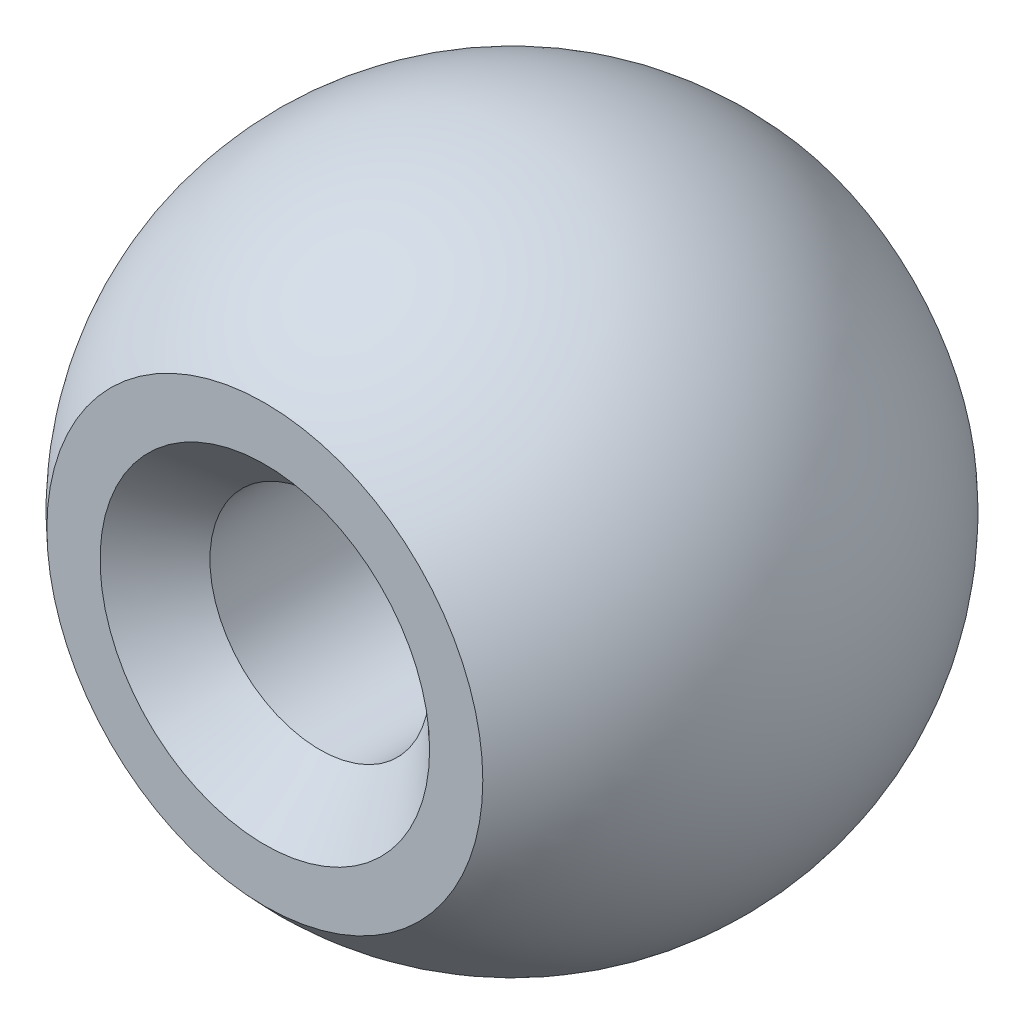
SolidWorks part; units mm, degrees
material "AISI 1020"
ref_plane "Front Plane" through (0, 0, 0) normal (0, 0, 1) x (1, 0, 0)
ref_plane "Top Plane" through (0, 0, 0) normal (0, 1, 0) x (1, 0, 0)
ref_plane "Right Plane" through (0, 0, 0) normal (1, 0, 0) x (0, 0, -1)
sketch "Sketch1" plane through (0, 0, 0) normal (1, 0, 0) x (0, 0, -1)
  line L0 (-9.663, 0) -> (9.663, 0) construction
  line L3 (-4.5, 3.9686) -> (-4.5, 0)
  line L5 (4.5, 3.9686) -> (4.5, 0)
  line L6 (0, -5) -> (0, 5) construction
  line L7 (-4.5, 0) -> (4.5, 0) construction
  line L9 (-4.5, 0) -> (4.5, 0)
  arc A2 (4.5, 3.9686) -> (-4.5, 3.9686) centre (0, 0) ccw
  point P4 (0, 0)
  dimension "D1" = 6
  dimension "D2" = 4.5
  dimension "D4" = 9
revolve "Revolve1" add sketch "Sketch1" angle 360 about L0
sketch "Sketch2" plane through (0, 0, 4.5) normal (0, 0, 1) x (1, 0, 0)
  circle A0 centre (0, 0) radius 2
  dimension "D1" = 4
extrude "Cut-Extrude1" cut sketch "Sketch2" against normal through all
chamfer "Chamfer1" distance 1 angle 45 1 edges at (2, 0, 4.5)
